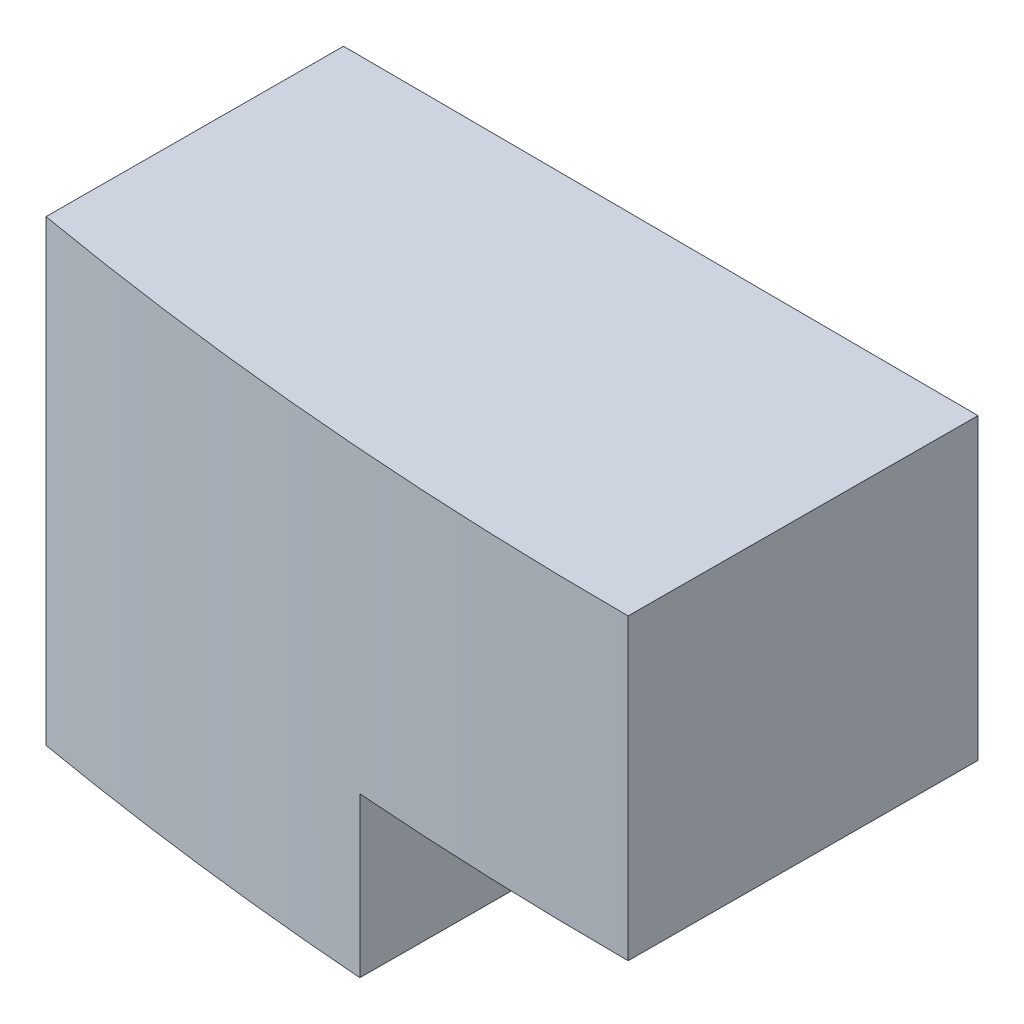
SolidWorks part; units mm, degrees
ref_plane "Plano frontal" through (0, 0, 0) normal (0, 0, 1) x (1, 0, 0)
ref_plane "Plano superior" through (0, 0, 0) normal (0, 1, 0) x (1, 0, 0)
ref_plane "Plano direito" through (0, 0, 0) normal (1, 0, 0) x (0, 0, -1)
sketch "Esboço1" plane through (0, 0, 0) normal (0, 1, 0) x (1, 0, 0)
  line L0 (0, 0) -> (0, -75) construction
  line L10 (0, -75) -> (0.0293, -68)
  line L11 (0.0293, -68) -> (-12.7706, -67.9464)
  line L12 (-12.7706, -67.9464) -> (-12.7955, -73.9004)
  arc A2 (-12.7955, -73.9004) -> (0, -75) centre (0, 0) ccw
  dimension "D1" = 75
  dimension "D4" = 12.8
  dimension "D2" = 7
  dimension "D3" = 0.24
extrude "Bloco" add sketch "Esboço1" along normal blind 9.2
sketch "Esboço3" plane through (-0.2848, 0, 67.9987) normal (0.0042, 0, -1) x (-1, 0, -0.0042)
  line L0 (-0.3142, 9.2) -> (-0.3142, 0) construction
  line L1 (-0.3142, 3.2) -> (5.2858, 3.2)
  line L2 (-0.3142, 3.2) -> (-0.3142, 0)
  line L3 (-0.3142, 0) -> (5.2858, 0)
  line L4 (5.2858, 3.2) -> (5.2858, 0)
  line L5 (-0.3142, 0) -> (12.4858, 0) construction
  line L6 (-0.3142, 9.2) -> (12.4858, 9.2) construction
  dimension "D1" = 6
  dimension "D2" = 5.6
extrude "Rasgo do Encaixe" cut sketch "Esboço3" against normal through all
